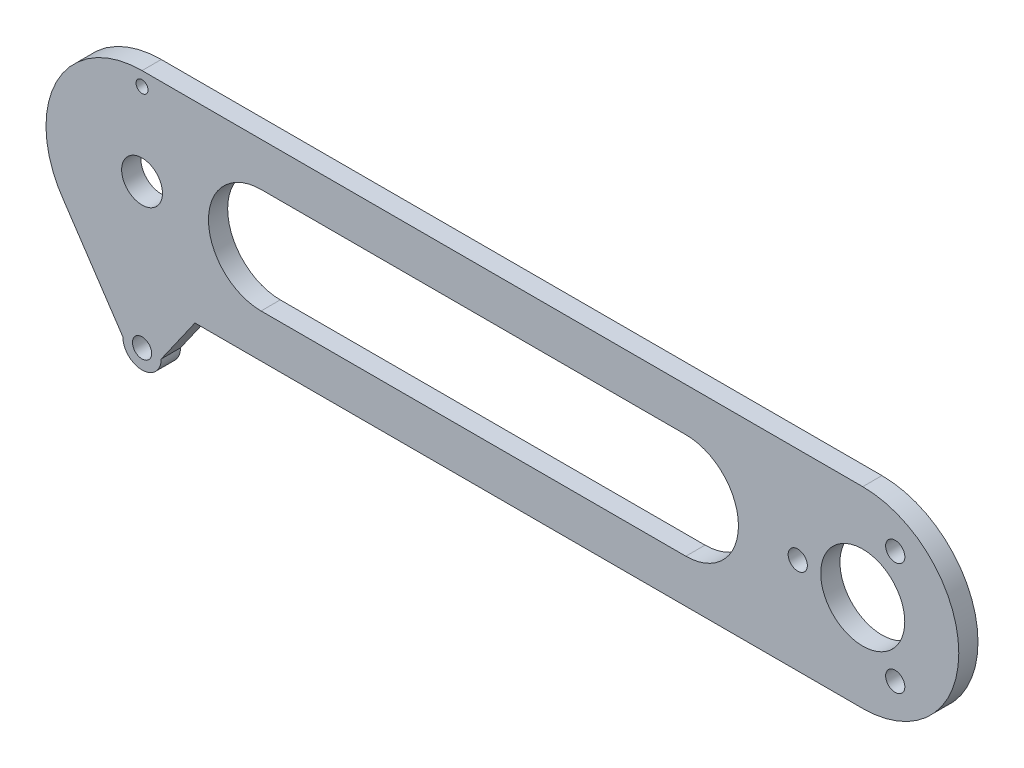
SolidWorks part; units mm, degrees
other "标注1"
sketch "草图6" plane through (-21, -34, 4) normal (0, 0, 1) x (1, 0, 0)
other "标注2"
sketch "草图7" plane through (-21, -34, 4) normal (0, 0, 1) x (1, 0, 0)
ref_plane "前视基准面" through (0, 0, 0) normal (0, 0, 1) x (1, 0, 0)
ref_plane "上视基准面" through (0, 0, 0) normal (0, 1, 0) x (1, 0, 0)
ref_plane "右视基准面" through (0, 0, 0) normal (1, 0, 0) x (0, 0, -1)
sketch "草图1" plane through (0, 0, 0) normal (0, 0, 1) x (1, 0, 0)
  line L7 (23.7835, 0) -> (112.2306, 0) construction
  line L12 (23.7835, 10.9539) -> (112.2306, 10.9539)
  line L13 (23.7835, -10.9539) -> (112.2306, -10.9539)
  line L19 (-1, 0) -> (-1, -30) construction
  line L20 (-5, -30) -> (-17.2082, -11.7173)
  line L59 (0, 32.5) -> (-18, 32.5) construction
  line L61 (3, -30) -> (10.0145, -20)
  line L63 (-1, 20) -> (-1, 17.12) construction
  line L64 (-1, 20) -> (149.0643, 20)
  line L66 (149.0643, -20) -> (10.0145, -20)
  circle A0 centre (-1, 0) radius 4.25
  arc A9 (-1, 20) -> (-1, -20) centre (-1, 0) ccw construction
  circle A13 centre (149.0643, 0) radius 8.75
  circle A18 centre (149.0643, 0) radius 13.53 construction
  arc A22 (149.0643, 20) -> (149.0643, -20) centre (149.0643, 0) cw
  arc A25 (23.7835, 10.9539) -> (23.7835, -10.9539) centre (23.7835, 0) ccw
  arc A26 (112.2306, -10.9539) -> (112.2306, 10.9539) centre (112.2306, 0) ccw
  circle A27 centre (135.5343, 0) radius 2
  circle A28 centre (155.8293, 11.7173) radius 2
  circle A29 centre (155.8293, -11.7173) radius 2
  circle A30 centre (-1, -30) radius 2
  circle A31 centre (-1, -30) radius 4 construction
  arc A32 (-17.2082, -11.7173) -> (-1, 20) centre (-1, 0) cw
  arc A33 (-5, -30) -> (3, -30) centre (-1, -30) ccw
  circle A34 centre (-1, 17.12) radius 1.25
  point P14 (68.007, 0)
  dimension "D1" = 8.5
  dimension "D2" = 3
  dimension "D3" = 17.5
extrude "凸台-拉伸1" add sketch "草图1" along normal blind 4
sketch "草图4" plane through (0, 0, 4) normal (0, 0, 1) x (1, 0, 0)
  circle A0 centre (-1, 0) radius 5
sketch "草图5" plane through (0, 0, 0) normal (0, 0, -1) x (-1, 0, 0)
  circle A0 centre (1, 0) radius 5
